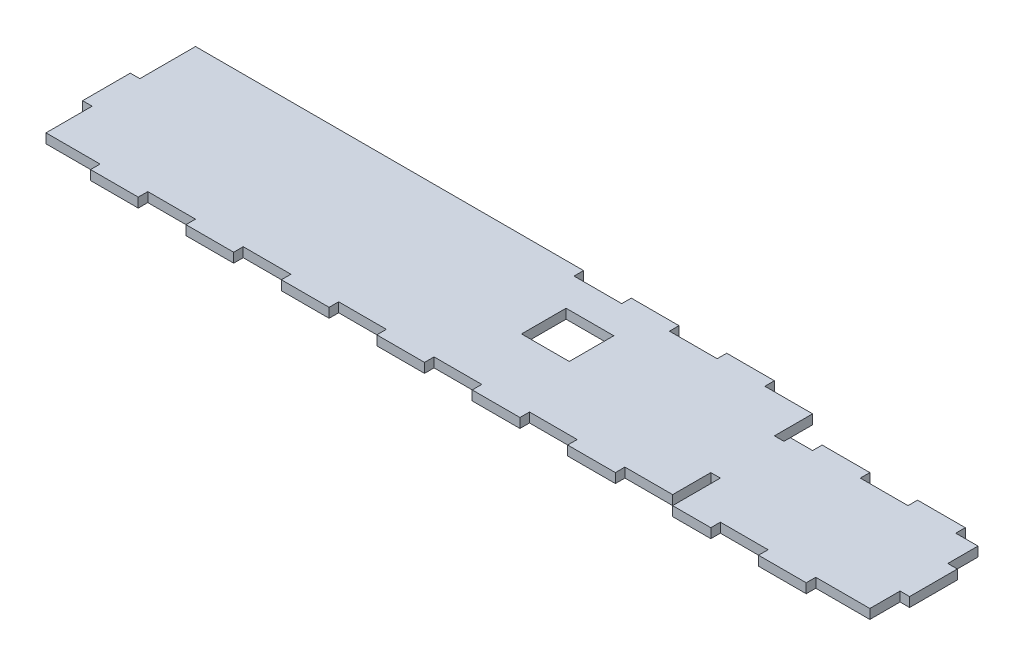
SolidWorks part; units mm, degrees
ref_plane "Alzado" through (0, 0, 0) normal (0, 0, 1) x (1, 0, 0)
ref_plane "Planta" through (0, 0, 0) normal (0, 1, 0) x (1, 0, 0)
ref_plane "Vista lateral" through (0, 0, 0) normal (1, 0, 0) x (0, 0, -1)
sketch "Croquis1" plane through (0, 0, 0) normal (0, 1, 0) x (1, 0, 0)
  line L0 (125, 50) -> (3, 50)
  line L1 (20, 50) -> (35, 50)
  line L2 (197, 3) -> (200, 3)
  line L3 (20, 0) -> (35, 0)
  line L4 (265, 12.5) -> (265, 27.5)
  line L5 (255, 40) -> (240, 40)
  line L6 (0, 25) -> (0, 32.5)
  line L7 (0, 32.5) -> (3, 32.5)
  line L8 (3, 32.5) -> (3, 47)
  line L9 (200, 15) -> (203, 15)
  line L10 (110, 47) -> (95, 47) construction
  line L11 (95, 47) -> (95, 50) construction
  line L12 (95, 50) -> (80, 50)
  line L13 (80, 50) -> (80, 47) construction
  line L14 (80, 47) -> (65, 47) construction
  line L15 (65, 47) -> (65, 50) construction
  line L16 (65, 50) -> (50, 50)
  line L17 (50, 50) -> (50, 47) construction
  line L18 (50, 47) -> (35, 47) construction
  line L19 (35, 47) -> (35, 50) construction
  line L20 (35, 50) -> (20, 50)
  line L21 (20, 50) -> (20, 47) construction
  line L22 (20, 47) -> (3, 47) construction
  line L23 (185, 47) -> (196.5, 47)
  line L24 (185, 50) -> (185, 47)
  line L25 (170, 47) -> (170, 50)
  line L26 (155, 47) -> (170, 47)
  line L27 (155, 50) -> (155, 47)
  line L28 (140, 47) -> (140, 50)
  line L29 (125, 47) -> (140, 47)
  line L30 (125, 50) -> (125, 47)
  line L31 (110, 47) -> (110, 50) construction
  line L32 (0, 25) -> (0, 17.5)
  line L33 (203, 15) -> (203, 0)
  line L34 (0, 17.5) -> (3, 17.5)
  line L35 (3, 17.5) -> (3, 3)
  line L36 (225, 40) -> (210, 40)
  line L37 (140, 3) -> (125, 3)
  line L38 (125, 3) -> (125, 0)
  line L39 (125, 0) -> (110, 0)
  line L40 (110, 0) -> (110, 3)
  line L41 (110, 3) -> (95, 3)
  line L42 (95, 3) -> (95, 0)
  line L43 (95, 0) -> (80, 0)
  line L44 (80, 0) -> (80, 3)
  line L45 (80, 3) -> (65, 3)
  line L46 (65, 3) -> (65, 0)
  line L47 (65, 0) -> (50, 0)
  line L48 (50, 0) -> (50, 3)
  line L49 (50, 3) -> (35, 3)
  line L50 (35, 3) -> (35, 0)
  line L51 (35, 0) -> (20, 0)
  line L52 (20, 0) -> (20, 3)
  line L53 (20, 3) -> (3, 3)
  line L54 (245, 3) -> (262, 3)
  line L55 (245, 0) -> (245, 3)
  line L56 (230, 3) -> (230, 0)
  line L57 (215, 3) -> (230, 3)
  line L58 (215, 0) -> (215, 3)
  line L59 (3, 50) -> (3, 47)
  line L60 (185, 3) -> (197, 3)
  line L61 (185, 0) -> (185, 3)
  line L62 (170, 3) -> (170, 0)
  line L63 (155, 3) -> (170, 3)
  line L64 (155, 0) -> (155, 3)
  line L65 (140, 3) -> (140, 0)
  line L66 (255, 40) -> (240, 40)
  line L67 (200, 35) -> (203, 35)
  line L68 (225, 37) -> (240, 37)
  line L69 (240, 37) -> (240, 40)
  line L70 (240, 40) -> (255, 40)
  line L71 (255, 40) -> (255, 37)
  line L72 (255, 37) -> (262, 37)
  line L73 (210, 37) -> (203, 37)
  line L74 (210, 40) -> (210, 37)
  line L75 (225, 37) -> (225, 40)
  line L76 (203, 35) -> (203, 37)
  line L78 (265, 20) -> (265, 27.5)
  line L79 (265, 27.5) -> (262, 27.5)
  line L80 (262, 27.5) -> (262, 37)
  line L81 (265, 20) -> (265, 12.5)
  line L82 (265, 12.5) -> (262, 12.5)
  line L83 (262, 12.5) -> (262, 3)
  line L85 (196.5, 47) -> (200, 47)
  line L87 (200, 35) -> (200, 37)
  line L89 (200, 15) -> (200, 3)
  line L90 (0, 17.5) -> (0, 32.5)
  line L91 (50, 0) -> (65, 0)
  line L92 (80, 0) -> (95, 0)
  line L93 (110, 0) -> (125, 0)
  line L94 (140, 0) -> (155, 0)
  line L95 (170, 0) -> (185, 0)
  line L96 (203, 0) -> (215, 0)
  line L97 (230, 0) -> (245, 0)
  line L98 (170, 50) -> (185, 50)
  line L99 (140, 50) -> (155, 50)
  line L100 (50, 50) -> (65, 50)
  line L101 (80, 50) -> (95, 50)
  line L102 (110, 50) -> (125, 50)
  line L103 (200, 47) -> (200, 37)
  dimension "D3" = 17
  dimension "D4" = 3
  dimension "D5" = 7.5
  dimension "D6" = 3
  dimension "D7" = 11.5
  dimension "D8" = 15
  dimension "D9" = 15
  dimension "D10" = 15
  dimension "D11" = 15
  dimension "D12" = 15
  dimension "D13" = 15
  dimension "D14" = 7.5
  dimension "D15" = 15
  dimension "D16" = 3
  dimension "D17" = 15
  dimension "D18" = 15
  dimension "D19" = 15
  dimension "D20" = 15
  dimension "D21" = 15
  dimension "D22" = 15
  dimension "D23" = 15
  dimension "D24" = 2
  dimension "D25" = 7
  dimension "D26" = 15
  dimension "D27" = 7.5
  dimension "D28" = 3
  dimension "D29" = 7.5
  dimension "D30" = 3
  dimension "D31" = 3
  dimension "D32" = 3
  dimension "D33" = 15
  dimension "D34" = 15
  dimension "D35" = 15
  dimension "D36" = 15
  dimension "D37" = 12
  dimension "D38" = 3
  dimension "D39" = 12
  dimension "D40" = 15
  dimension "D41" = 15
  dimension "D42" = 17
  dimension "D43" = 3
  dimension "D44" = 3
  dimension "D45" = 3
  dimension "D46" = 17
  dimension "D47" = 3
  dimension "D48" = 3
  dimension "D49" = 12
  dimension "D50" = 3
  dimension "D51" = 3
  dimension "D52" = 3
  dimension "D53" = 3
extrude "Saliente-Extruir1" add sketch "Croquis1" along normal blind 3
sketch "Sketch1" plane through (0, 3, 0) normal (0, 1, 0) x (1, 0, 0)
  line L0 (125, 50) -> (3, 50) construction
  line L1 (132.5, 37) -> (147.5, 37)
  line L2 (132.5, 37) -> (132.5, 23)
  line L3 (132.5, 23) -> (147.5, 23)
  line L4 (147.5, 37) -> (147.5, 23)
  line L5 (132.5, 37) -> (147.5, 23) construction
  line L6 (132.5, 23) -> (147.5, 37) construction
  line L7 (0, 17.5) -> (0, 32.5) construction
  point P0 (140, 30)
  dimension "D1" = 15
  dimension "D2" = 14
  dimension "D3" = 20
  dimension "D4" = 140
extrude "Cut-Extrude1" cut sketch "Sketch1" against normal blind 10
